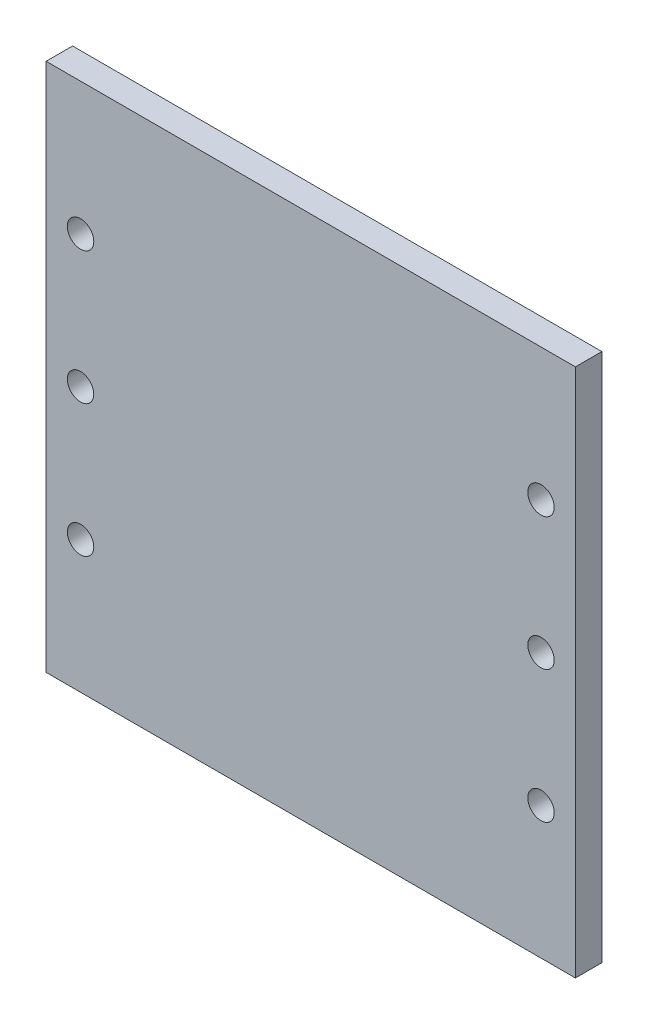
SolidWorks part; units mm, degrees
material "6063-T6"
ref_plane "Front Plane" through (0, 0, 0) normal (0, 0, 1) x (1, 0, 0)
ref_plane "Top Plane" through (0, 0, 0) normal (0, 1, 0) x (1, 0, 0)
ref_plane "Right Plane" through (0, 0, 0) normal (1, 0, 0) x (0, 0, -1)
sketch "Sketch1" plane through (0, 0, 0) normal (0, 0, 1) x (1, 0, 0)
  line L1 (0, 0) -> (100, 0)
  line L2 (0, 0) -> (0, 100)
  line L3 (0, 100) -> (100, 100)
  line L4 (100, 0) -> (100, 100)
  circle A0 centre (6.5, 75) radius 2.5
  circle A1 centre (6.5, 50) radius 2.5
  circle A2 centre (6.5, 25) radius 2.5
  circle A3 centre (93.5, 25) radius 2.5
  circle A4 centre (93.5, 50) radius 2.5
  circle A5 centre (93.5, 75) radius 2.5
  dimension "D3" = 5
  dimension "D4" = 5
  dimension "D5" = 5
  dimension "D6" = 5
  dimension "D7" = 5
  dimension "D8" = 5
  dimension "D9" = 25
  dimension "D10" = 25
  dimension "D11" = 50
  dimension "D12" = 25
  dimension "D13" = 50
  dimension "D14" = 25
  dimension "D15" = 6.5
  dimension "D16" = 6.5
  dimension "D17" = 6.5
  dimension "D18" = 6.5
  dimension "D19" = 6.5
  dimension "D20" = 6.5
  dimension "D1" = 100
  dimension "D2" = 100
extrude "Boss-Extrude1" add sketch "Sketch1" along normal blind 5
